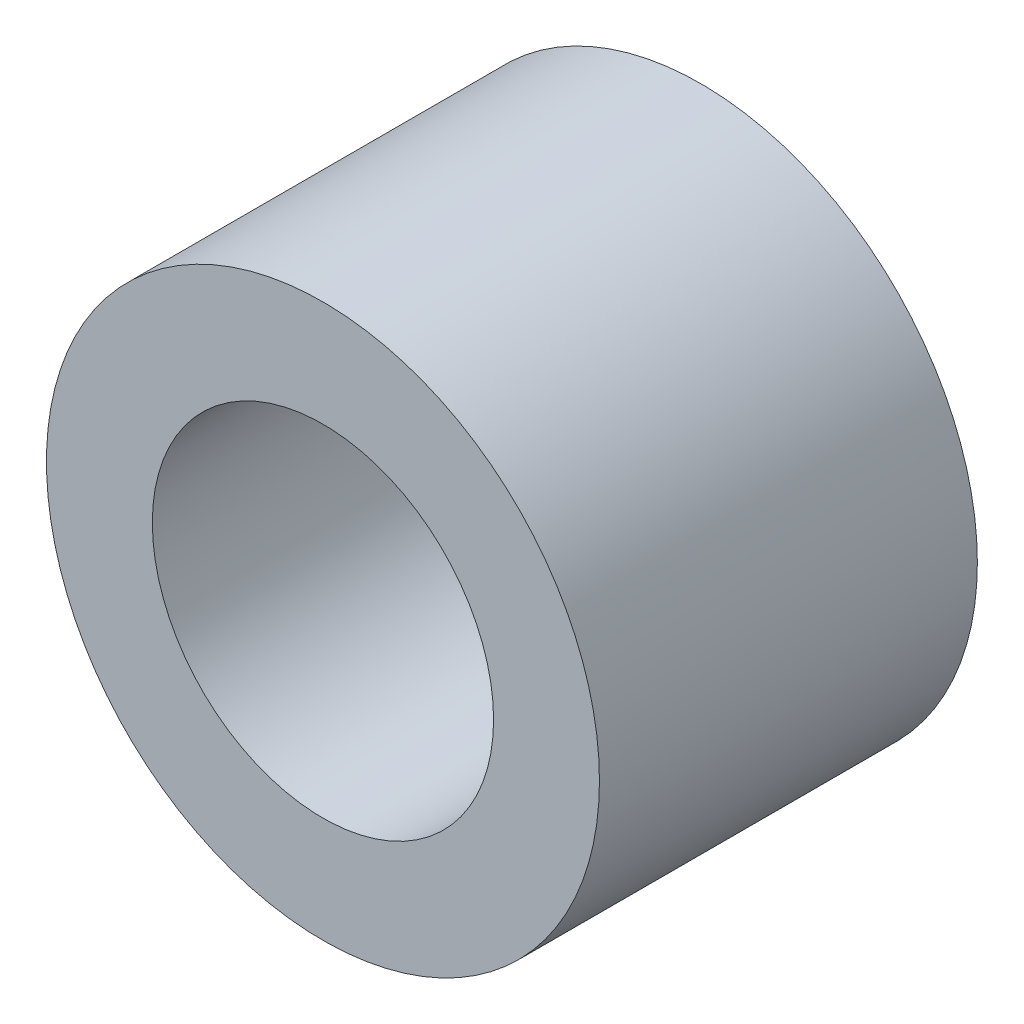
SolidWorks part; units mm, degrees
ref_plane "Front Plane" through (0, 0, 0) normal (0, 0, 1) x (1, 0, 0)
ref_plane "Top Plane" through (0, 0, 0) normal (0, 1, 0) x (1, 0, 0)
ref_plane "Right Plane" through (0, 0, 0) normal (1, 0, 0) x (0, 0, -1)
sketch "Sketch1" plane through (0, 0, 0) normal (0, 0, 1) x (1, 0, 0)
  circle A0 centre (0, 0) radius 20.2565
  circle A1 centre (0, 0) radius 12.5
  dimension "D1" = 40.513
  dimension "D2" = 24.9999
extrude "Boss-Extrude1" add sketch "Sketch1" along normal blind 27.686
shell "Shell1" thickness 0.254
sketch "Sketch2" plane through (0, 0, 0) normal (0, 0, -1) x (-1, 0, 0)
  circle A0 centre (0, 0) radius 12.5
extrude "Boss-Extrude2" add sketch "Sketch2" against normal blind 0.254
sketch "Sketch3" plane through (0, 0, 27.686) normal (0, 0, 1) x (1, 0, 0)
  circle A0 centre (0, 0) radius 20.0025
  circle A1 centre (0, 0) radius 12.754
extrude "Boss-Extrude3" add sketch "Sketch3" against normal blind 0.254
